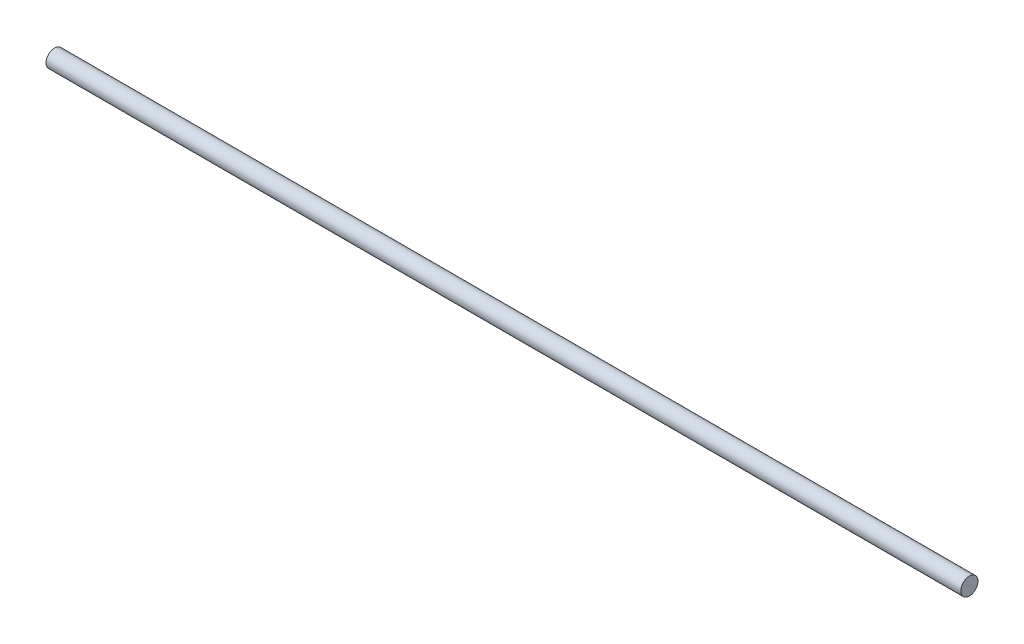
SolidWorks part; units mm, degrees
ref_plane "Front Plane" through (0, 0, 0) normal (0, 0, 1) x (1, 0, 0)
ref_plane "Top Plane" through (0, 0, 0) normal (0, 1, 0) x (1, 0, 0)
ref_plane "Right Plane" through (0, 0, 0) normal (1, 0, 0) x (0, 0, -1)
sketch "Sketch1" plane through (0, 0, 0) normal (1, 0, 0) x (0, 0, -1)
  circle A0 centre (0, 0) radius 3.81
  dimension "D1" = 7.62
extrude "Boss-Extrude1" add sketch "Sketch1" along normal blind 403.9695
equation "\"Load Force\"= 400"
equation "\"Young's Modulus E\"= 10000000"
equation "\"Max Deflection\"= 0.009"
equation "\"Diameter D\"= 0.30"
equation "\"Yield Strength\"= 40000"
equation "\"Area\"= \"Diameter D\" ^ 2 * pi / 4"
equation "\"L\"= \"Max Deflection\" * \"Area\" * \"Young's Modulus E\" / \"Load Force\"''''''"
equation "\"D1@Sketch1\"=0.30in"
equation "\"D1@Boss-Extrude1\"=\"L\""
